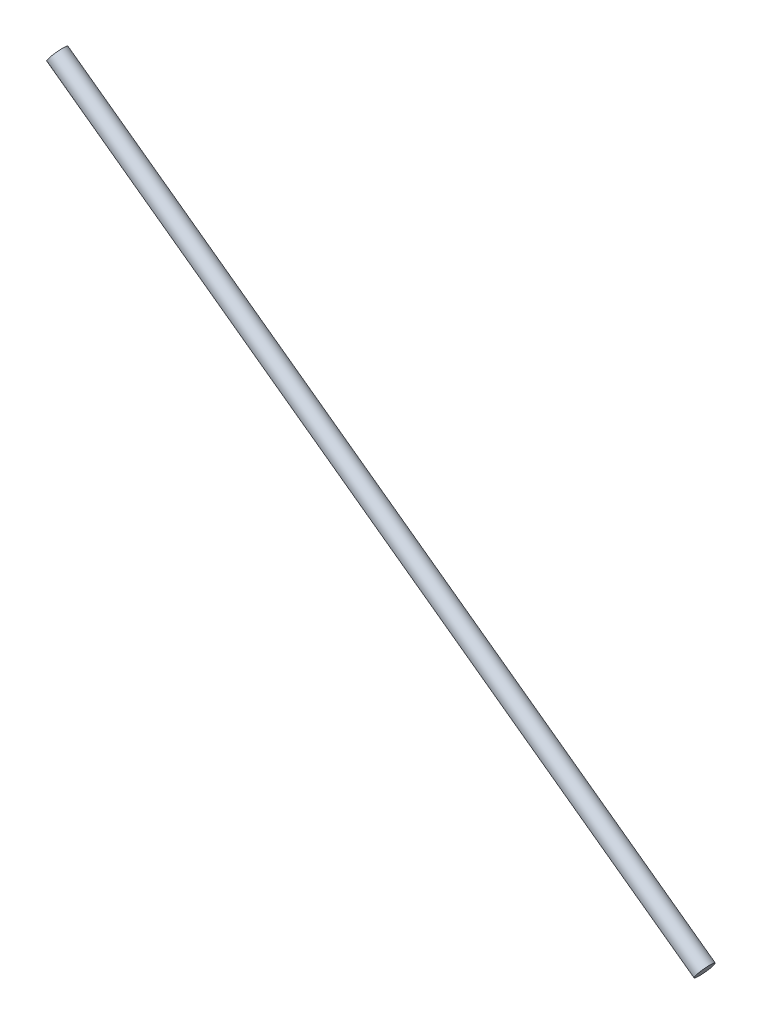
SolidWorks part; units mm, degrees
ref_plane "Front Plane" through (0, 0, 0) normal (0, 0, 1) x (1, 0, 0)
ref_plane "Top Plane" through (0, 0, 0) normal (0, 1, 0) x (1, 0, 0)
ref_plane "Right Plane" through (0, 0, 0) normal (1, 0, 0) x (0, 0, -1)
sketch "Sketch2" plane through (0, 0, 0) normal (0, 0, 1) x (1, 0, 0)
  line L0 (178.7928, 134.6028) -> (72.7649, 211.6366)
  line L1 (182.0288, -132.2517) -> (225, 0) construction
  line L2 (225, 0) -> (182.0288, 132.2517) construction
  line L3 (182.0288, 132.2517) -> (69.5288, 213.9877) construction
  line L4 (69.5288, 213.9877) -> (-69.5288, 213.9877) construction
  line L5 (-69.5288, 213.9877) -> (-182.0288, 132.2517) construction
  line L6 (-182.0288, 132.2517) -> (-225, 0) construction
  line L7 (-225, 0) -> (-182.0288, -132.2517) construction
  line L8 (-182.0288, -132.2517) -> (-69.5288, -213.9877) construction
  line L9 (-69.5288, -213.9877) -> (69.5288, -213.9877) construction
  line L10 (69.5288, -213.9877) -> (182.0288, -132.2517) construction
  line L11 (112.5, 81.736) -> (69.5288, 213.9877) construction
  line L12 (69.5288, 213.9877) -> (-69.5288, 213.9877) construction
  line L13 (-69.5288, 213.9877) -> (-112.5, 81.736) construction
  line L14 (-112.5, 81.736) -> (0, 0) construction
  line L15 (0, 0) -> (112.5, 81.736) construction
  circle A0 centre (0, 0) radius 225 construction
  circle A1 centre (0, 0) radius 213.9877 construction
  circle A2 centre (0, 118.2895) radius 95.6982 construction
  point P16 (0, 225)
  point P24 (0, 213.9877)
  dimension "D1" = 450
  dimension "D2" = 4
  dimension "D3" = 4
ref_plane "Plane1" through (72.7649, 211.6366, 0) normal (-0.809, 0.5878, 0) x (0, 0, 1)
sketch "Sketch3" plane through (72.7649, 211.6366, 0) normal (-0.809, 0.5878, 0) x (0, 0, 1)
  circle A0 centre (0, 0) radius 1.5
  dimension "D1" = 3
sweep "Sweep1" add profiles "Sketch3" path "Sketch2"
